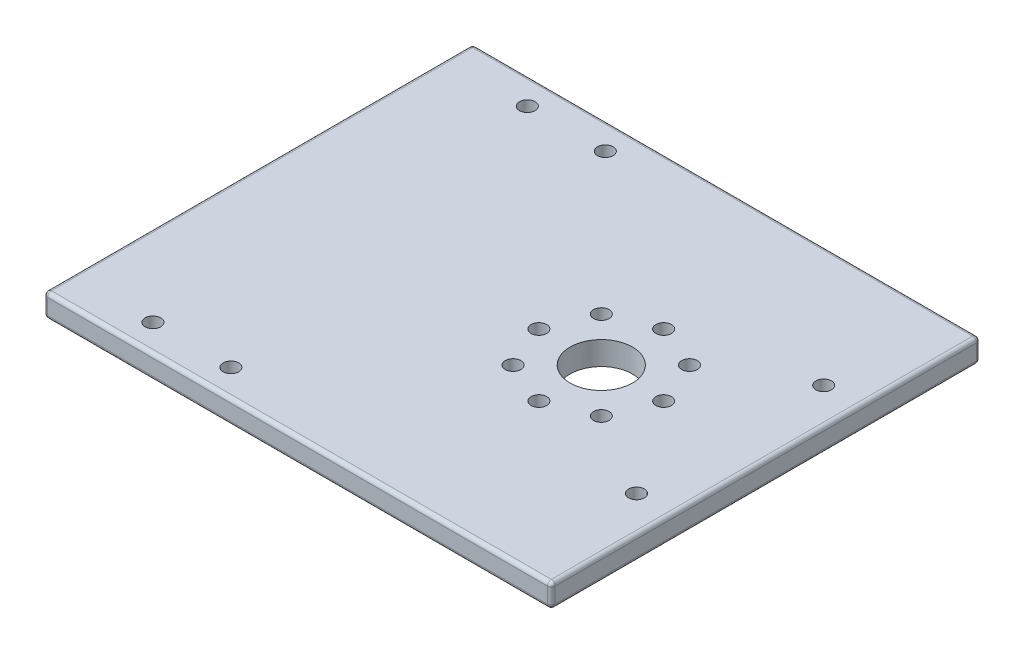
SolidWorks part; units mm, degrees
ref_plane "Front Plane" through (0, 0, 0) normal (0, 0, 1) x (1, 0, 0)
ref_plane "Top Plane" through (0, 0, 0) normal (0, 1, 0) x (1, 0, 0)
ref_plane "Right Plane" through (0, 0, 0) normal (1, 0, 0) x (0, 0, -1)
sketch "Sketch1" plane through (0, 548.353, 0) normal (0, 1, 0) x (1, 0, 0)
  line L0 (0, 0) -> (-24.486, 0) construction
  line L5 (-43.9857, 27.5) -> (21.0942, 27.5)
  line L6 (-43.9857, 27.5) -> (-43.9857, -27.5)
  line L7 (-43.9857, -27.5) -> (21.0942, -27.5)
  line L8 (21.0942, 27.5) -> (21.0942, -27.5)
  circle A3 centre (0, 0) radius 4
  dimension "D1" = 8
  dimension "D2" = 55
extrude "Boss-Extrude1" add sketch "Sketch1" along normal blind 3
sketch "Sketch2" plane through (0, 551.353, 0) normal (0, 1, 0) x (1, 0, 0)
  circle A0 centre (0, 8) radius 1
  circle A1 centre (5.6569, 5.6569) radius 1
  circle A2 centre (8, 0) radius 1
  circle A3 centre (5.6569, -5.6569) radius 1
  circle A4 centre (0, -8) radius 1
  circle A5 centre (-5.6569, -5.6569) radius 1
  circle A6 centre (-8, 0) radius 1
  circle A7 centre (-5.6569, 5.6569) radius 1
extrude "Cut-Extrude1" cut sketch "Sketch2" against normal up to surface (3 mm away) up to face at (-11.4458, 548.353, 0)
fillet "Fillet1" radius 0.5 12 edges at (-43.9857, 551.353, 0) (-43.9857, 548.353, 0) (-11.4458, 551.353, -27.5) (-43.9857, 549.853, -27.5) (-11.4458, 548.353, -27.5) (21.0942, 551.353, 0) (21.0942, 549.853, -27.5) (21.0942, 548.353, 0) (-43.9857, 549.853, 27.5) (-11.4458, 551.353, 27.5) (21.0942, 549.853, 27.5) (-11.4458, 548.353, 27.5)
sketch "Sketch3" plane through (0, 551.353, 0) normal (0, 1, 0) x (1, 0, 0)
  circle A0 centre (-33.4857, -24) radius 1
  circle A1 centre (-23.4857, -24) radius 1
  circle A2 centre (16.5143, -12) radius 1
  circle A3 centre (16.5143, 12) radius 1
  circle A4 centre (-23.4857, 24) radius 1
  circle A5 centre (-33.4857, 24) radius 1
extrude "Cut-Extrude2" cut sketch "Sketch3" against normal through all
